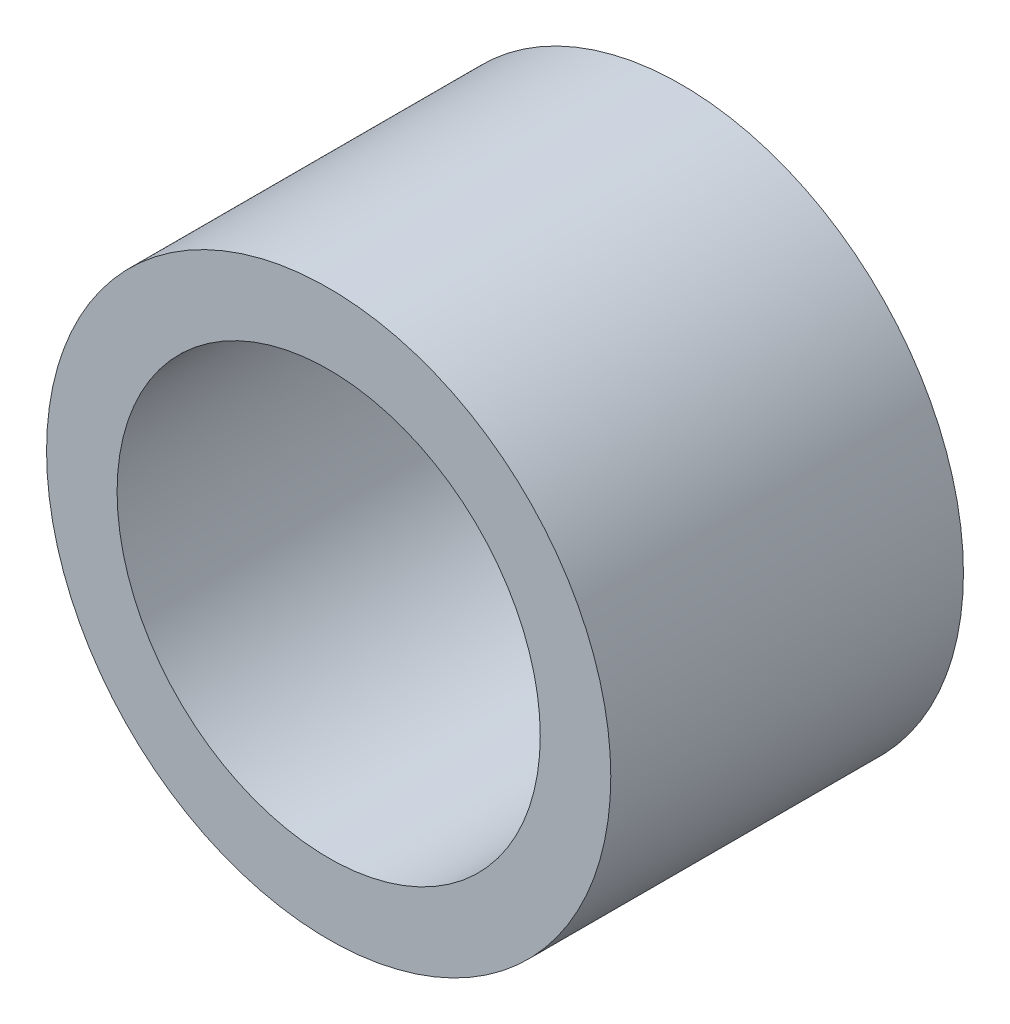
SolidWorks part; units mm, degrees
ref_plane "Front Plane" through (0, 0, 0) normal (0, 0, 1) x (1, 0, 0)
ref_plane "Top Plane" through (0, 0, 0) normal (0, 1, 0) x (1, 0, 0)
ref_plane "Right Plane" through (0, 0, 0) normal (1, 0, 0) x (0, 0, -1)
sketch "Sketch1" plane through (0, 0, 0) normal (0, 0, 1) x (1, 0, 0)
  circle A0 centre (0, 0) radius 2
  dimension "D1" = 4
extrude "Boss-Extrude1" add sketch "Sketch1" along normal blind 2.5
sketch "Sketch2" plane through (0, 0, 0) normal (0, 0, 1) x (1, 0, 0)
  circle A0 centre (0, 0) radius 1.5
  dimension "D1" = 3
extrude "Cut-Extrude1" cut sketch "Sketch2" along normal blind 2.5
